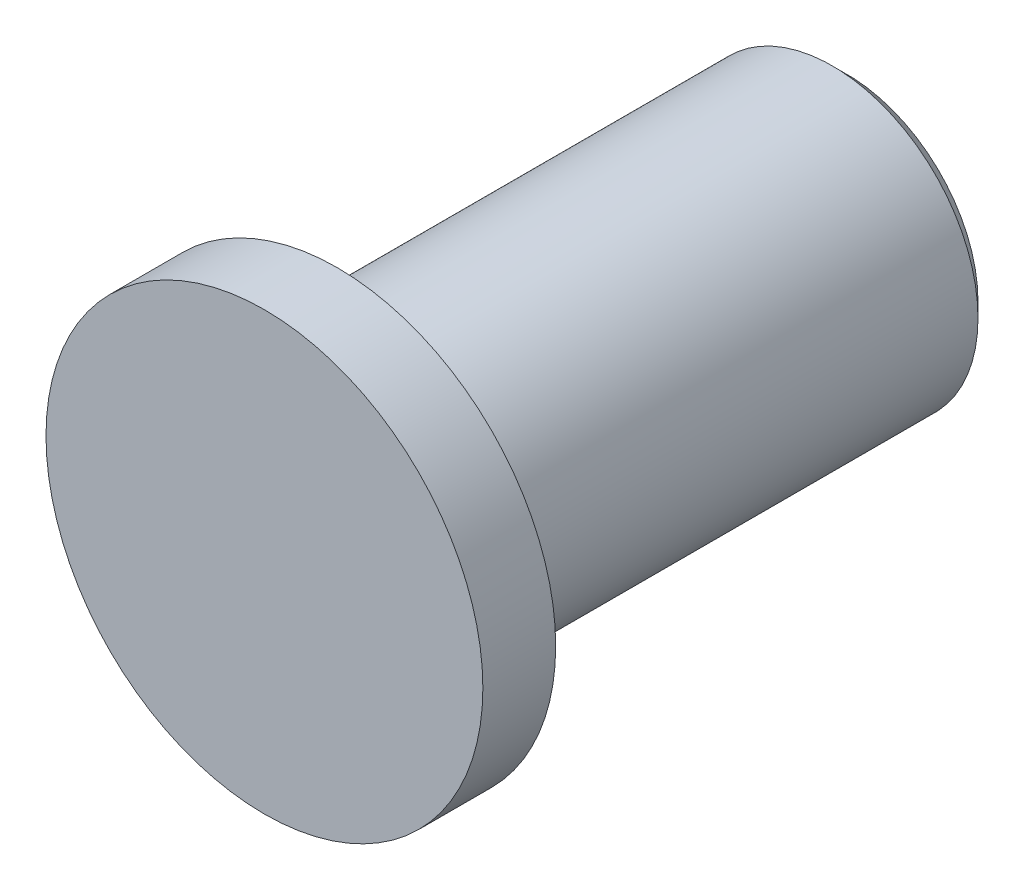
SolidWorks part; units mm, degrees
ref_plane "Front Plane" through (0, 0, 0) normal (0, 0, 1) x (1, 0, 0)
ref_plane "Top Plane" through (0, 0, 0) normal (0, 1, 0) x (1, 0, 0)
ref_plane "Right Plane" through (0, 0, 0) normal (1, 0, 0) x (0, 0, -1)
sketch "Sketch1" plane through (0, 0, 0) normal (0, 0, 1) x (1, 0, 0)
  circle A0 centre (0, 0) radius 10
  dimension "D1" = 20
extrude "Boss-Extrude1" add sketch "Sketch1" against normal blind 35
sketch "Sketch2" plane through (0, 0, 0) normal (0, 0, 1) x (1, 0, 0)
  circle A0 centre (0, 0) radius 15
  dimension "D1" = 30
extrude "Boss-Extrude2" add sketch "Sketch2" along normal blind 5
chamfer "Chamfer1" distance 1 angle 45 1 edges at (10, 0, -35)
